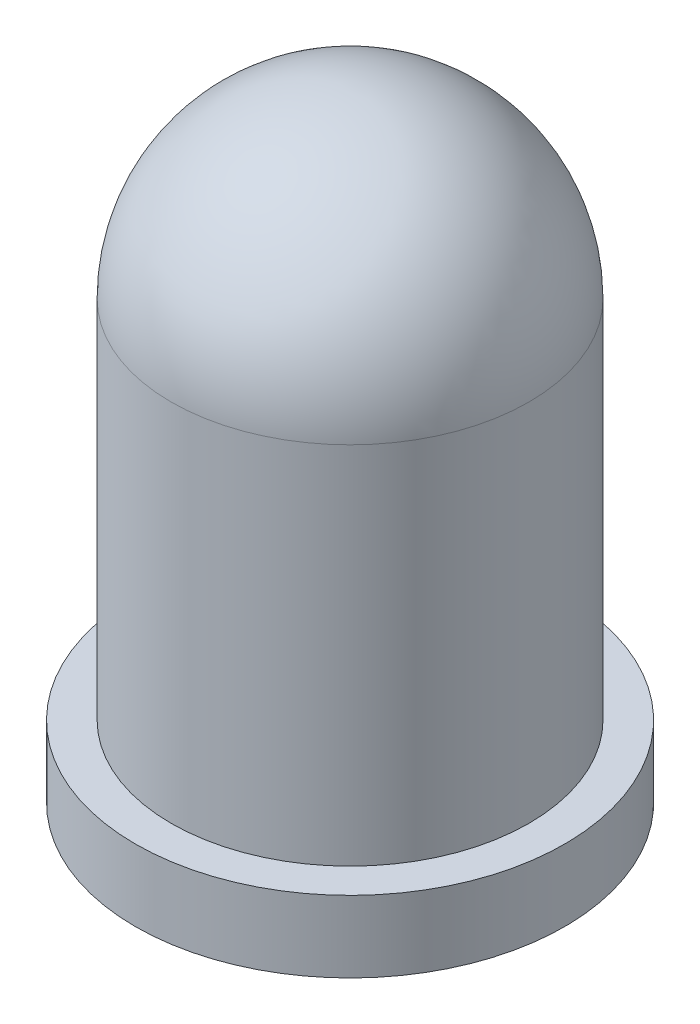
SolidWorks part; units mm, degrees
ref_plane "Front Plane" through (0, 0, 0) normal (0, 0, 1) x (1, 0, 0)
ref_plane "Top Plane" through (0, 0, 0) normal (0, 1, 0) x (1, 0, 0)
ref_plane "Right Plane" through (0, 0, 0) normal (1, 0, 0) x (0, 0, -1)
sketch "Sketch1" plane through (0, 0, 0) normal (0, 1, 0) x (1, 0, 0)
  circle A0 centre (0, 0) radius 2.5
  dimension "D1" = 5
extrude "Boss-Extrude1" add sketch "Sketch1" along normal blind 8.6
sketch "Sketch2" plane through (0, 0, 0) normal (0, 0, 1) x (1, 0, 0)
  line L0 (-2.5, 8.6) -> (-2.5, 0) construction
  line L1 (2.5, 8.6) -> (-2.5, 8.6) construction
  line L2 (0, 8.7915) -> (0, 5.6825) construction
  line L3 (-2.5, 6.1) -> (-3.7057, 6.1)
  line L4 (-3.7057, 6.1) -> (-3.7057, 8.7915)
  line L5 (-3.7057, 8.7915) -> (0, 8.7915)
  line L6 (0, 8.6) -> (0, 8.7915)
  arc A0 (-2.5, 6.1) -> (0, 8.6) centre (0, 6.1) cw
revolve "Cut-Revolve1" cut sketch "Sketch2" angle 360 about L2
sketch "Sketch3" plane through (0, 0, 0) normal (0, 1, 0) x (1, 0, 0)
  circle A0 centre (0, 0) radius 3
  dimension "D1" = 6
extrude "Boss-Extrude2" add sketch "Sketch3" along normal blind 1
